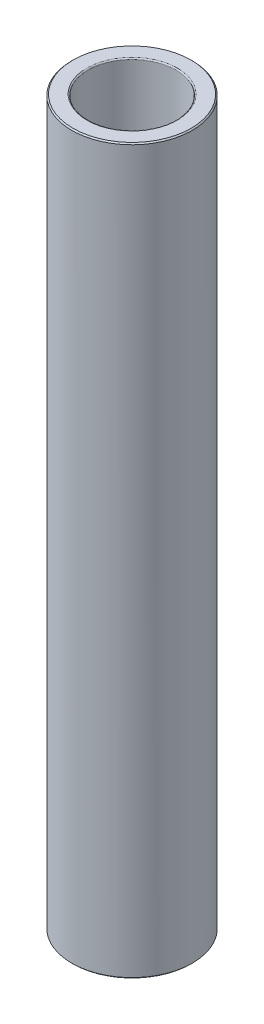
SolidWorks part; units mm, degrees
ref_plane "Front Plane" through (0, 0, 0) normal (0, 0, 1) x (1, 0, 0)
ref_plane "Top Plane" through (0, 0, 0) normal (0, 1, 0) x (1, 0, 0)
ref_plane "Right Plane" through (0, 0, 0) normal (1, 0, 0) x (0, 0, -1)
sketch "Sketch1" plane through (0, 0, 0) normal (0, 1, 0) x (1, 0, 0)
  circle A0 centre (0, 0) radius 12.7
  circle A1 centre (0, 0) radius 9.271
  dimension "D1" = 25.4
  dimension "D2" = 18.542
extrude "Boss-Extrude1" add sketch "Sketch1" along normal blind 152.4 contours A1 | A0
chamfer "Chamfer1" distance 0.254 angle 45 2 edges at (0, 0, 12.7) (0, 152.4, 12.7)
fillet "Fillet1" radius 0.254 2 edges at (0, 0, 9.271) (0, 152.4, 9.271)
